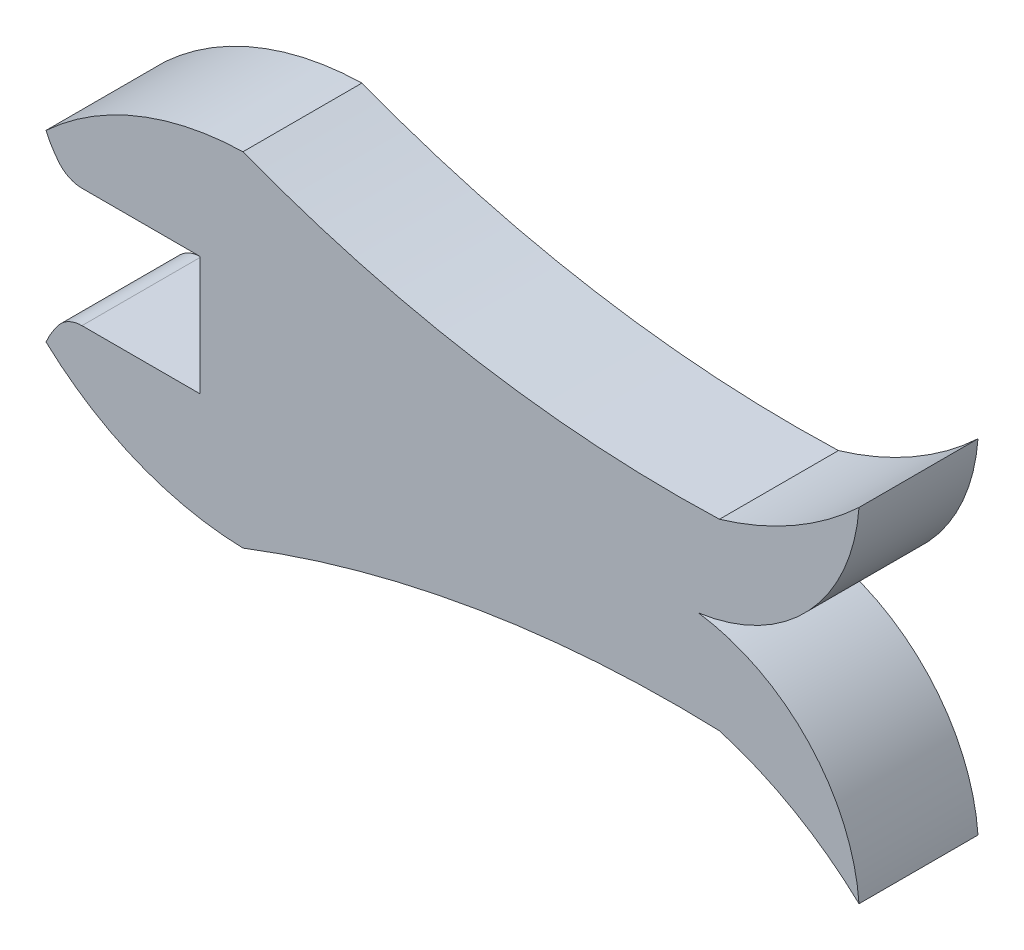
SolidWorks part; units mm, degrees
ref_plane "Front Plane" through (0, 0, 0) normal (0, 0, 1) x (1, 0, 0)
ref_plane "Top Plane" through (0, 0, 0) normal (0, 1, 0) x (1, 0, 0)
ref_plane "Right Plane" through (0, 0, 0) normal (1, 0, 0) x (0, 0, -1)
sketch "Sketch1" plane through (0, 0, 0) normal (0, 0, 1) x (1, 0, 0)
  line L0 (121.5236, 0) -> (120.0116, 0)
  line L1 (121.5236, -1.524) -> (121.5236, 0)
  line L2 (121.5236, -0.762) -> (122.4093, -0.762) construction
  line L4 (121.5236, -1.524) -> (120.0116, -1.524)
  arc A0 (119.7159, -1.6647) -> (119.5509, -1.9356) centre (120.6277, -2.4057) ccw
  arc A1 (119.5509, -1.9356) -> (122.0741, -2.9603) centre (122.1654, 0.883) ccw
  arc A2 (122.0741, -2.9603) -> (128.1778, -1.9356) centre (127.6322, -17.3756) cw
  arc A3 (128.1778, -1.9356) -> (129.9651, -2.9603) centre (126.9082, -6.2209) cw
  arc A4 (129.9651, -2.9603) -> (127.909, -0.762) centre (127.5748, -3.1353) ccw
  arc A5 (119.7159, 0.1407) -> (119.5509, 0.4116) centre (120.6277, 0.8817) cw
  arc A6 (129.9651, 1.4363) -> (127.909, -0.762) centre (127.5748, 1.6113) cw
  arc A7 (128.1778, 0.4116) -> (129.9651, 1.4363) centre (126.9082, 4.6969) ccw
  arc A8 (122.0741, 1.4363) -> (128.1778, 0.4116) centre (127.6322, 15.8516) ccw
  arc A9 (119.5509, 0.4116) -> (122.0741, 1.4363) centre (122.1654, -2.407) cw
  arc A10 (119.7159, -1.6647) -> (120.0116, -1.524) centre (120.0116, -1.905) cw
  arc A11 (120.0116, 0) -> (119.7159, 0.1407) centre (120.0116, 0.381) cw
  dimension "D1" = 0.381
  dimension "D2" = 0.381
extrude "Boss-Extrude1" add sketch "Sketch1" along normal blind 1.524
